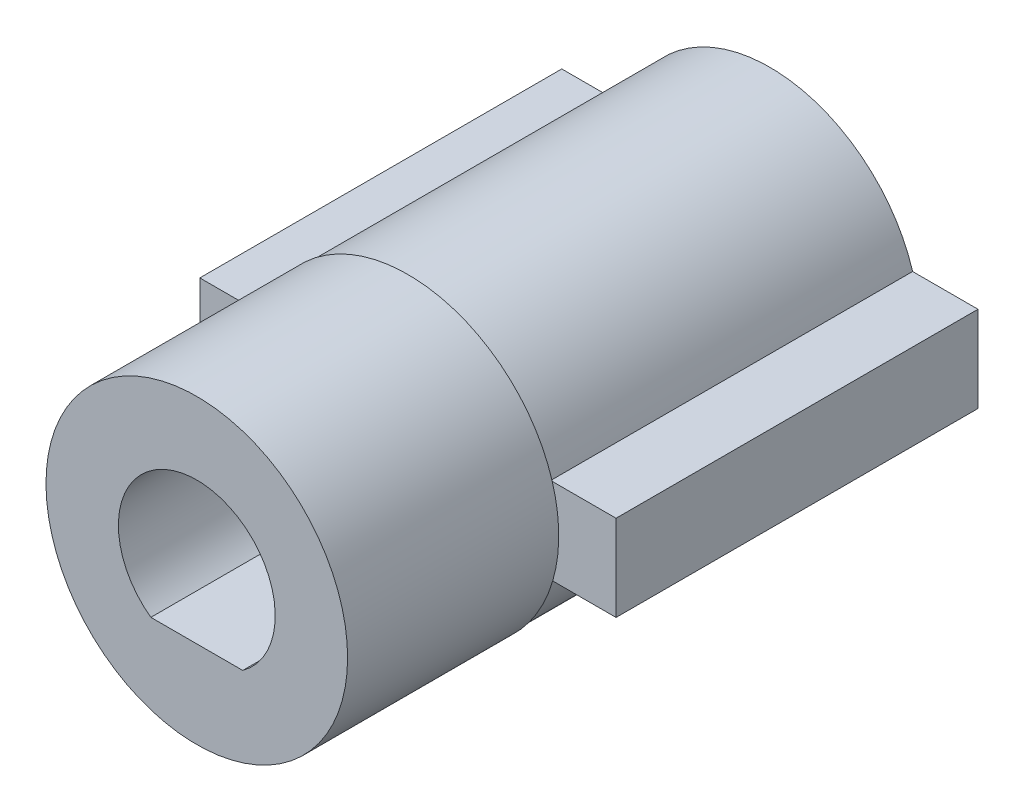
SolidWorks part; units mm, degrees
ref_plane "Ön Düzlem" through (0, 0, 0) normal (0, 0, 1) x (1, 0, 0)
ref_plane "Üst Düzlem" through (0, 0, 0) normal (0, 1, 0) x (1, 0, 0)
ref_plane "Sağ Düzlem" through (0, 0, 0) normal (1, 0, 0) x (0, 0, -1)
sketch "Çizim1" plane through (0, 0, 0) normal (0, 0, 1) x (1, 0, 0)
  line L0 (4.7325, 1.4512) -> (6.9, 1.4512)
  line L1 (4.7483, -1.3988) -> (6.9, -1.3988)
  line L4 (-6.9, -1.3988) -> (-4.7483, -1.3988)
  line L5 (-6.9, -1.3988) -> (-6.9, 1.4512)
  line L6 (6.9, -1.3988) -> (6.9, 1.4512)
  line L7 (-6.9, 1.4512) -> (-4.7325, 1.4512)
  line L8 (1.5237, -2.1067) -> (-1.5237, -2.1067)
  arc A0 (-4.7483, -1.3988) -> (4.7483, -1.3988) centre (0, 0) ccw
  arc A1 (4.7325, 1.4512) -> (-4.7325, 1.4512) centre (0, 0) ccw
  arc A2 (1.5237, -2.1067) -> (-1.5237, -2.1067) centre (0, 0) ccw
  dimension "D1" = 4.95
  dimension "D5" = 2.6
  dimension "D2" = 6.9
  dimension "D3" = 6.9
  dimension "D4" = 2.85
extrude "Yükseklik-Ekstrüzyon1" add sketch "Çizim1" along normal blind 12
ref_plane "Düzlem1" through (0, 0, 12) normal (0, 0, 1) x (1, 0, 0)
sketch "Çizim3" plane through (0, 0, 12) normal (0, 0, 1) x (1, 0, 0)
  line L0 (-1.5237, -2.1067) -> (1.5237, -2.1067)
  circle A0 centre (0, 0) radius 5
  arc A1 (1.5237, -2.1067) -> (-1.5237, -2.1067) centre (0, 0) ccw
extrude "Yükseklik-Ekstrüzyon3" add sketch "Çizim3" along normal blind 7
sketch "Çizim2" plane through (0, 0, 0) normal (0, 0, 1) x (1, 0, 0)
  circle A0 centre (0, 0) radius 2.7019
  circle A1 centre (0, 0) radius 1.49
extrude "Yükseklik-Ekstrüzyon2" add sketch "Çizim2" along normal blind 8
